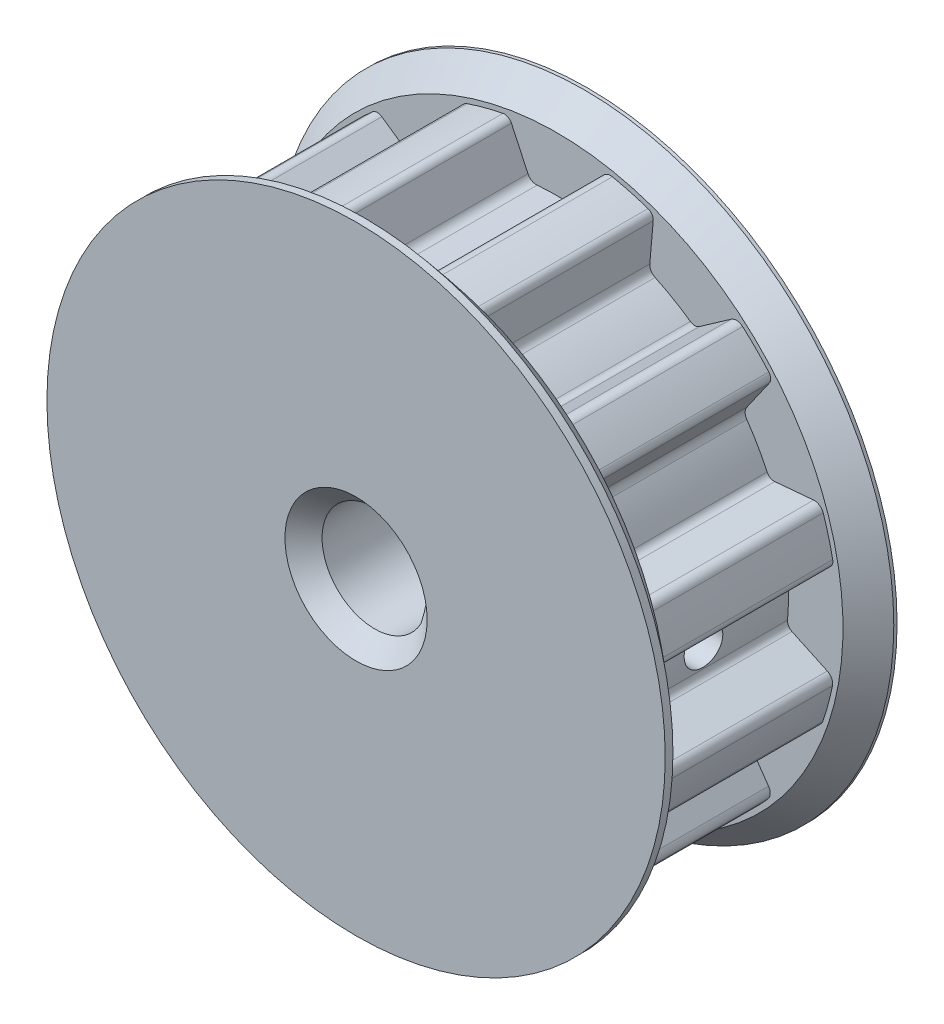
SolidWorks part; units mm, degrees
ref_plane "정면" through (0, 0, 0) normal (0, 0, 1) x (1, 0, 0)
ref_plane "윗면" through (0, 0, 0) normal (0, 1, 0) x (1, 0, 0)
ref_plane "우측면" through (0, 0, 0) normal (1, 0, 0) x (0, 0, -1)
sketch "스케치1" plane through (0, 0, 0) normal (0, 0, 1) x (1, 0, 0)
  line L0 (13.7295, 11.3315) -> (12.2791, 9.2601)
  line L1 (17.5559, 2.9486) -> (15.264, 1.8799)
  line L2 (15.2005, -1.8503) -> (17.4848, -2.9155)
  line L3 (14.0892, 5.9978) -> (16.6, 6.2175)
  line L4 (11.3315, -13.7295) -> (9.2601, -12.2791)
  line L5 (5.9978, -14.0892) -> (6.2175, -16.6)
  line L6 (12.2389, -9.2026) -> (13.6845, -11.2673)
  line L7 (16.6781, -6.2244) -> (14.159, -6.004)
  line L8 (-15.2005, 1.8503) -> (-17.4848, 2.9155)
  line L9 (-17.5559, -2.9486) -> (-15.264, -1.8799)
  line L10 (-16.6781, 6.2244) -> (-14.159, 6.004)
  line L11 (-12.2389, 9.2026) -> (-13.6845, 11.2673)
  line L12 (-14.0892, -5.9978) -> (-16.6, -6.2175)
  line L13 (-13.7295, -11.3315) -> (-12.2791, -9.2601)
  line L14 (-9.2026, -12.2389) -> (-11.2673, -13.6845)
  line L15 (-6.2244, -16.6781) -> (-6.004, -14.159)
  line L16 (-1.8503, -15.2005) -> (-2.9155, -17.4848)
  line L17 (2.9486, -17.5559) -> (1.8799, -15.264)
  line L18 (-5.9978, 14.0892) -> (-6.2175, 16.6)
  line L19 (-11.3315, 13.7295) -> (-9.2601, 12.2791)
  line L20 (9.2026, 12.2389) -> (11.2673, 13.6845)
  line L21 (6.2244, 16.6781) -> (6.004, 14.159)
  line L22 (1.8503, 15.2005) -> (2.9155, 17.4848)
  line L23 (-2.9486, 17.5559) -> (-1.8799, 15.264)
  line L24 (-21, 0) -> (21, 0) construction
  line L25 (0, -21) -> (0, 21) construction
  arc A0 (13.5918, 6.2861) -> (12.2786, 8.5724) centre (0, 0) ccw
  arc A1 (17.8195, -3.5773) -> (17.4848, -2.9155) centre (17.2312, -3.4593) ccw
  arc A2 (15.264, 1.8799) -> (14.9198, 1.2847) centre (15.5176, 1.3361) ccw
  arc A3 (17.5559, 2.9486) -> (17.8352, 3.498) centre (17.3446, 3.4018) ccw
  arc A4 (14.9138, -1.352) -> (15.2005, -1.8503) centre (15.4118, -1.3971) ccw
  arc A5 (14.9138, -1.352) -> (14.9198, 1.2847) centre (0, 0) ccw
  arc A6 (13.5918, 6.2861) -> (14.0892, 5.9978) centre (14.0456, 6.4959) ccw
  arc A7 (9.2601, -12.2791) -> (8.5724, -12.2786) centre (8.9159, -12.7706) ccw
  arc A8 (6.2861, -13.5918) -> (8.5724, -12.2786) centre (0, 0) ccw
  arc A9 (6.2861, -13.5918) -> (5.9978, -14.0892) centre (6.4959, -14.0456) ccw
  arc A10 (11.3315, -13.7295) -> (11.947, -13.6967) centre (11.6183, -13.3199) ccw
  arc A11 (5.8117, -17.2208) -> (6.2175, -16.6) centre (5.6198, -16.6523) ccw
  arc A12 (12.0078, 13.6434) -> (11.2673, 13.6845) centre (11.6114, 13.193) ccw
  arc A13 (13.6434, -12.0078) -> (13.6845, -11.2673) centre (13.193, -11.6114) ccw
  arc A14 (16.6781, -6.2244) -> (17.1947, -5.8882) centre (16.7217, -5.7263) ccw
  arc A15 (14.159, -6.004) -> (13.5632, -6.3474) centre (14.1067, -6.6017) ccw
  arc A16 (12.2398, -8.6278) -> (13.5632, -6.3474) centre (0, 0) ccw
  arc A17 (12.2398, -8.6278) -> (12.2389, -9.2026) centre (12.6484, -8.9159) ccw
  arc A18 (-14.9138, 1.352) -> (-15.2005, 1.8503) centre (-15.4118, 1.3971) ccw
  arc A19 (-14.9138, 1.352) -> (-14.9198, -1.2847) centre (0, 0) ccw
  arc A20 (12.2791, 9.2601) -> (12.2786, 8.5724) centre (12.7706, 8.9159) ccw
  arc A21 (-17.5559, -2.9486) -> (-17.8352, -3.498) centre (-17.3446, -3.4018) ccw
  arc A22 (-16.6781, 6.2244) -> (-17.1947, 5.8882) centre (-16.7217, 5.7263) ccw
  arc A23 (-14.159, 6.004) -> (-13.5632, 6.3474) centre (-14.1067, 6.6017) ccw
  arc A24 (-12.2398, 8.6278) -> (-13.5632, 6.3474) centre (0, 0) ccw
  arc A25 (-12.2398, 8.6278) -> (-12.2389, 9.2026) centre (-12.6484, 8.9159) ccw
  arc A26 (-13.6434, 12.0078) -> (-13.6845, 11.2673) centre (-13.193, 11.6114) ccw
  arc A27 (-17.2208, -5.8117) -> (-16.6, -6.2175) centre (-16.6523, -5.6198) ccw
  arc A28 (17.2208, 5.8117) -> (16.6, 6.2175) centre (16.6523, 5.6198) ccw
  arc A29 (-13.5918, -6.2861) -> (-12.2786, -8.5724) centre (0, 0) ccw
  arc A30 (-12.2791, -9.2601) -> (-12.2786, -8.5724) centre (-12.7706, -8.9159) ccw
  arc A31 (-13.7295, -11.3315) -> (-13.6967, -11.947) centre (-13.3199, -11.6183) ccw
  arc A32 (-13.5918, -6.2861) -> (-14.0892, -5.9978) centre (-14.0456, -6.4959) ccw
  arc A33 (13.7295, 11.3315) -> (13.6967, 11.947) centre (13.3199, 11.6183) ccw
  arc A34 (-12.0078, -13.6434) -> (-11.2673, -13.6845) centre (-11.6114, -13.193) ccw
  arc A35 (-8.6278, -12.2398) -> (-9.2026, -12.2389) centre (-8.9159, -12.6484) ccw
  arc A36 (-8.6278, -12.2398) -> (-6.3474, -13.5632) centre (0, 0) ccw
  arc A37 (-6.004, -14.159) -> (-6.3474, -13.5632) centre (-6.6017, -14.1067) ccw
  arc A38 (-6.2244, -16.6781) -> (-5.8882, -17.1947) centre (-5.7263, -16.7217) ccw
  arc A39 (-3.5773, -17.8195) -> (-2.9155, -17.4848) centre (-3.4593, -17.2312) ccw
  arc A40 (-1.352, -14.9138) -> (-1.8503, -15.2005) centre (-1.3971, -15.4118) ccw
  arc A41 (-1.352, -14.9138) -> (1.2847, -14.9198) centre (0, 0) ccw
  arc A42 (1.8799, -15.264) -> (1.2847, -14.9198) centre (1.3361, -15.5176) ccw
  arc A43 (2.9486, -17.5559) -> (3.498, -17.8352) centre (3.4018, -17.3446) ccw
  arc A44 (-5.8117, 17.2208) -> (-6.2175, 16.6) centre (-5.6198, 16.6523) ccw
  arc A45 (-6.2861, 13.5918) -> (-5.9978, 14.0892) centre (-6.4959, 14.0456) ccw
  arc A46 (-6.2861, 13.5918) -> (-8.5724, 12.2786) centre (0, 0) ccw
  arc A47 (-9.2601, 12.2791) -> (-8.5724, 12.2786) centre (-8.9159, 12.7706) ccw
  arc A48 (-11.3315, 13.7295) -> (-11.947, 13.6967) centre (-11.6183, 13.3199) ccw
  arc A49 (-17.8195, 3.5773) -> (-17.4848, 2.9155) centre (-17.2312, 3.4593) ccw
  arc A50 (-1.8799, 15.264) -> (-1.2847, 14.9198) centre (-1.3361, 15.5176) ccw
  arc A51 (8.6278, 12.2398) -> (9.2026, 12.2389) centre (8.9159, 12.6484) ccw
  arc A52 (8.6278, 12.2398) -> (6.3474, 13.5632) centre (0, 0) ccw
  arc A53 (6.004, 14.159) -> (6.3474, 13.5632) centre (6.6017, 14.1067) ccw
  arc A54 (6.2244, 16.6781) -> (5.8882, 17.1947) centre (5.7263, 16.7217) ccw
  arc A55 (3.5773, 17.8195) -> (2.9155, 17.4848) centre (3.4593, 17.2312) ccw
  arc A56 (-2.9486, 17.5559) -> (-3.498, 17.8352) centre (-3.4018, 17.3446) ccw
  arc A57 (1.352, 14.9138) -> (-1.2847, 14.9198) centre (0, 0) ccw
  arc A58 (1.352, 14.9138) -> (1.8503, 15.2005) centre (1.3971, 15.4118) ccw
  arc A59 (-15.264, -1.8799) -> (-14.9198, -1.2847) centre (-15.5176, -1.3361) ccw
  circle A60 centre (0, 0) radius 18.175
  point P153 (0, 6.5)
  point P154 (0, 6.5)
extrude "보스-돌출1" add sketch "스케치1" along normal mid plane 11 contours A3 A60 A28 L3 A6 A0 A20 L0 A33 A12 L20 A51 A52 A53 L21 A54 A55 L22 A58 A57 A50 L23 A56 A44 L18 A45 A46 A47 L19 A48 A26 L11 A25 A24 A23 L10 A22 A49 L8 A18 A19 A59 L9 A21 A27
sketch "스케치2" plane through (0, 0, 5.5) normal (0, 0, 1) x (1, 0, 0)
  circle A0 centre (0, 0) radius 20
  dimension "D1" = 40
extrude "보스-돌출2" add sketch "스케치2" along normal blind 2
chamfer "모따기1" distance 1.5 angle 50 1 edges at (20, 0, 5.5)
mirror "대칭 복사1" about plane through (0, 0, 0) normal (0, 0, 1) of "모따기1", "보스-돌출2"
sketch "스케치3" plane through (0, 0, -7.5) normal (0, 0, -1) x (-1, 0, 0)
  circle A0 centre (0, 0) radius 3.4
  dimension "D1" = 6.8
extrude "컷-돌출1" cut sketch "스케치3" against normal blind 30
chamfer "모따기2" distance 1.2 angle 45 2 edges at (3.4, 0, 7.5) (-3.4, 0, -7.5)
sketch "스케치4" plane through (0, 0, 0) normal (0, 0, 1) x (1, 0, 0)
  line L0 (3, 1.6) -> (3, -1.6)
  line L1 (-3.4, 0) -> (3, 0) construction
  circle A0 centre (0, 0) radius 3.4
  circle A1 centre (0, 0) radius 3.4 construction
  dimension "D1" = 6.4
extrude "보스-돌출3" add sketch "스케치4" along normal up to surface and the other way up to surface contours L0 A0
sketch "스케치5" plane through (3, 0, 0) normal (-1, 0, 0) x (0, 0, 1)
  circle A0 centre (0, 0) radius 1.25
  dimension "D1" = 2.5
sketch "스케치6" plane through (0, 0, 0) normal (1, 0, 0) x (0, 0, -1)
  circle A0 centre (0, 0) radius 1.25
  dimension "D1" = 2.5
extrude "컷-돌출3" cut sketch "스케치6" along normal blind 33
extrude "컷-돌출2" cut sketch "스케치5" against normal blind 20
